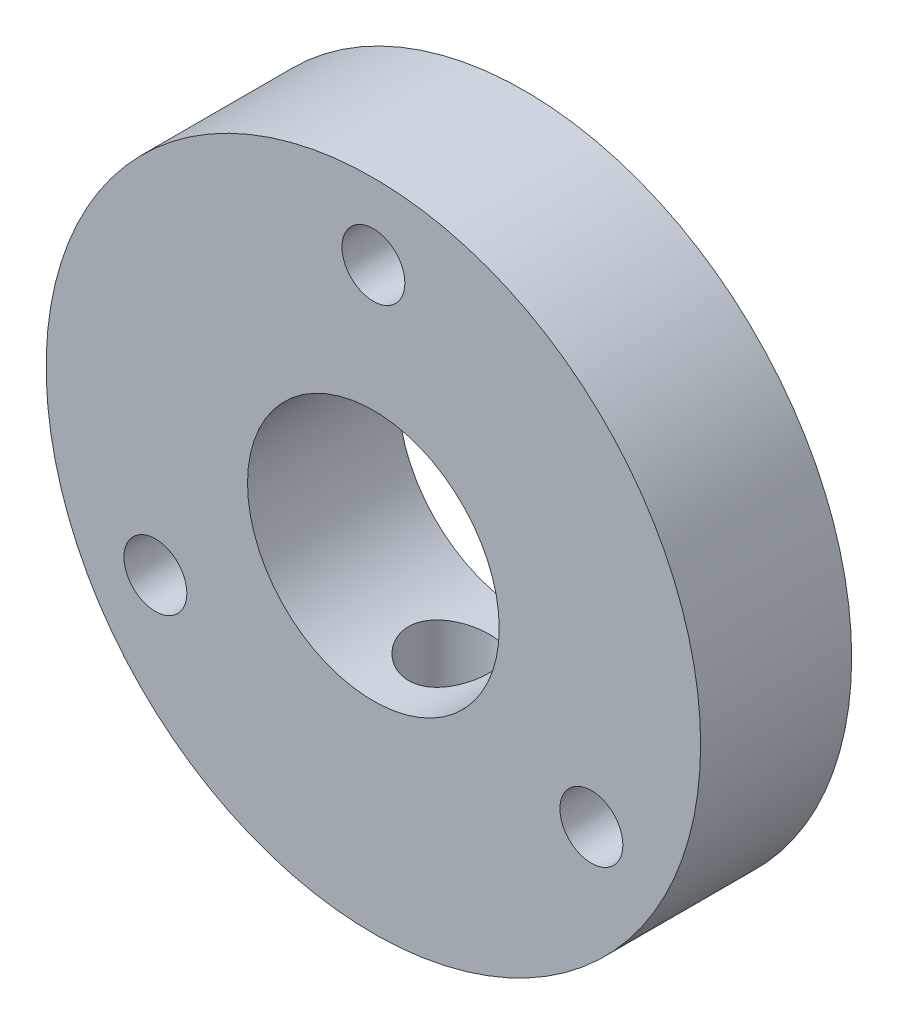
SolidWorks part; units mm, degrees
material "Нержавеющая сталь (ферритная)"
ref_plane "Спереди" through (0, 0, 0) normal (0, 0, 1) x (1, 0, 0)
ref_plane "Сверху" through (0, 0, 0) normal (0, 1, 0) x (1, 0, 0)
ref_plane "Справа" through (0, 0, 0) normal (1, 0, 0) x (0, 0, -1)
sketch "Model" plane through (0, 0, 0) normal (0, 0, 1) x (1, 0, 0)
  circle A133 centre (0, 0) radius 6.5
  dimension "D1" = 13
extrude "База" add sketch "Model" against normal mid plane 3
sketch "Эскиз3" plane through (0, 0, 1.5) normal (0, 0, 1) x (1, 0, 0)
  circle A2 centre (0, 0) radius 2.5
  dimension "D1" = 5
extrude "Вырез-Вытянуть1" cut sketch "Эскиз3" along direction (0, 0, 1) on the side against the normal through all
hole_wizard "Крепление шестерни M1.6" positions "Эскиз5" profile "Эскиз6" tap size "M1.6" standard "ISO" end condition through all
sketch "Эскиз5" plane through (0, 0, 1.5) normal (0, 0, 1) x (1, 0, 0)
  circle A0 centre (0, 0) radius 5 construction
  point P0 (0, 5)
  point P2 (4.3301, -2.5)
  point P4 (-4.3301, -2.5)
  dimension "D1" = 10
  dimension "D2" = 120
  dimension "D3" = 120
sketch "Эскиз6" plane through (0, 5, 1.5) normal (1, 0, 0) x (0, -1, 0)
  line L0 (0, 0) -> (0, 3)
  line L1 (0, 3) -> (0.625, 3)
  line L2 (0.625, 3) -> (0.625, 0)
  line L5 (0.625, 0) -> (0, 0)
  line L11 (0, -6.35) -> (0, 107.95) construction
  dimension "Диаметр проходного сверла" = 1.25
  dimension "Глубина проходного сверла" = 3
cosmetic thread "Отверстие резьбы1" parameters "D2"=1.6
cosmetic thread "Отверстие резьбы2" parameters "D2"=1.6
cosmetic thread "Отверстие резьбы3" parameters "D2"=1.6
hole_wizard "Крепление на вал M2" positions "Эскиз7" profile "Эскиз8" tap size "M2" standard "ISO"
sketch "Эскиз7" plane through (0, 0, 0) normal (0, 1, 0) x (1, 0, 0)
  point P0 (0, 0)
sketch "Эскиз8" plane through (0, 0, 0) normal (1, 0, 0) x (0, 0, 1)
  line L0 (0, 0) -> (0, 6.5)
  line L1 (0, 6.5) -> (0.8, 6.5)
  line L2 (0.8, 6.5) -> (0.8, 0)
  line L5 (0.8, 0) -> (0, 0)
  line L11 (0, -6.35) -> (0, 107.95) construction
  dimension "Диаметр проходного сверла" = 1.6
  dimension "Глубина проходного сверла" = 6.5
cosmetic thread "Отверстие резьбы4" parameters "D2"=2
